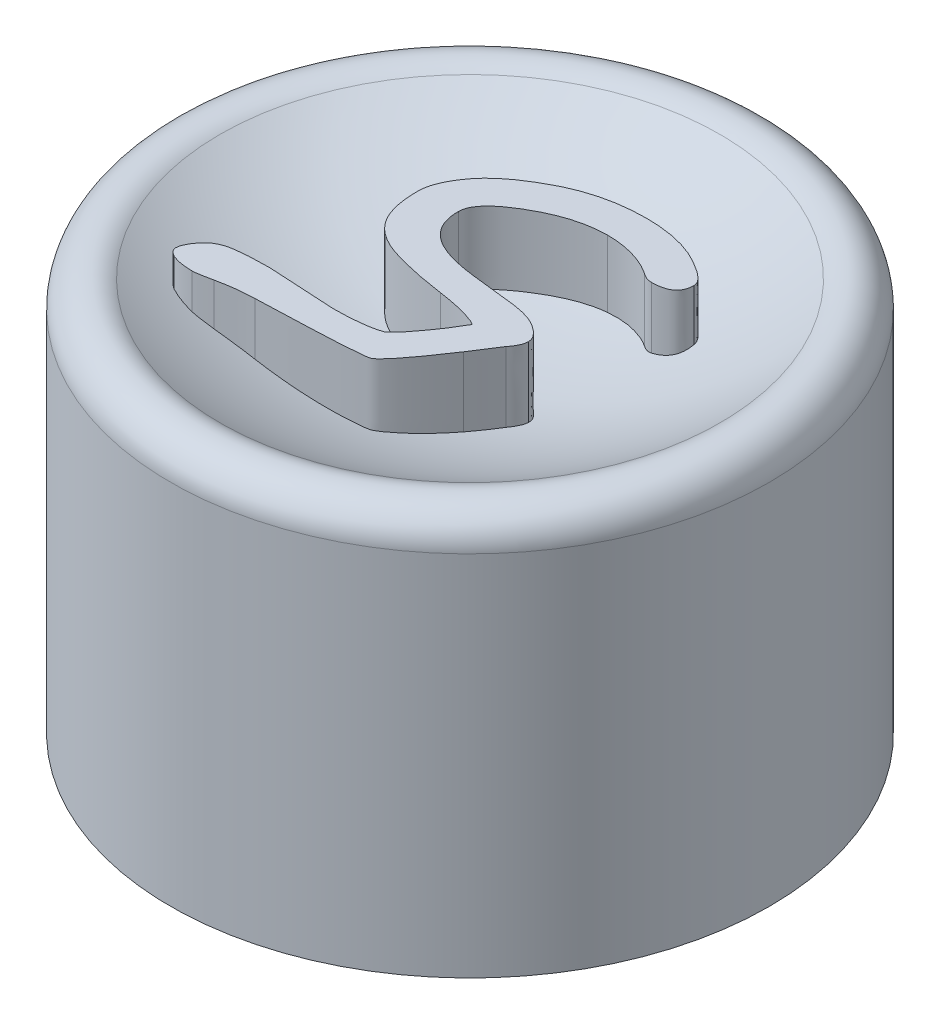
SolidWorks part; units mm, degrees
ref_plane "Front Plane" through (0, 0, 0) normal (0, 0, 1) x (1, 0, 0)
ref_plane "Top Plane" through (0, 0, 0) normal (0, 1, 0) x (1, 0, 0)
ref_plane "Right Plane" through (0, 0, 0) normal (1, 0, 0) x (0, 0, -1)
sketch "Sketch1" plane through (0, 0, 0) normal (0, 0, 1) x (1, 0, 0)
  line L0 (0, 0) -> (0, -66.4851) construction
  line L1 (55, 0) -> (-55, 0) construction
  line L2 (-1.5494, 0) -> (-1.5494, 3.048)
  line L3 (-1.5494, 3.048) -> (-0.762, 3.048)
  line L4 (-0.762, 3.048) -> (-0.762, 4.064)
  line L5 (-0.762, 4.064) -> (0, 4.064)
  line L6 (0, -55) -> (0, 55) construction
  line L7 (0, 4.064) -> (0, 5.08)
  line L8 (-4.7625, 5.842) -> (-4.7625, 0)
  line L9 (-4.7625, 0) -> (-3.4925, 0)
  line L10 (-3.4925, 0) -> (-3.4925, 4.064)
  line L11 (-3.4925, 4.064) -> (-2.0574, 4.064)
  line L12 (-2.0574, 4.064) -> (-2.0574, 0)
  line L13 (-2.0574, 0) -> (-1.5494, 0)
  line L14 (0, 5.08) -> (3.3062, 5.08) construction
  arc A0 (-4.7625, 5.842) -> (-3.976, 6.2669) centre (-4.2545, 5.842) cw
  arc A1 (-3.976, 6.2669) -> (0, 5.08) centre (0, 12.3333) ccw
  dimension "D4" = 1.524
  dimension "D5" = 6.35
  dimension "D9" = 0.508
  dimension "D1" = 9.525
  dimension "D2" = 3.0988
  dimension "D3" = 3.048
  dimension "D6" = 0.508
  dimension "D7" = 1.016
  dimension "D8" = 1.27
  dimension "D10" = 5.08
revolve "Revolve1" add sketch "Sketch1" angle 360 about L0
ref_plane "Plane1" through (0, 6.35, 0) normal (0, 1, 0) x (-1, 0, 0)
sketch "Sketch3" plane through (0, 6.35, 0) normal (0, 1, 0) x (-1, 0, 0)
  line L0 (-2.3812, -2.032) -> (2.3813, -2.032) construction
  line L1 (0, 0) -> (0, -7.9672) construction
  line L2 (0, 3.4925) -> (0, -3.4925) construction
  line L3 (3.4925, 0) -> (-3.4925, 0) construction
  text T0 "5" font "Segoe Print" height 4.7625
  dimension "D1" = 2.032
  dimension "D2" = 4.7625
extrude "Boss-Extrude1" add sketch "Sketch3" against normal up to surface (0.91 mm away)
